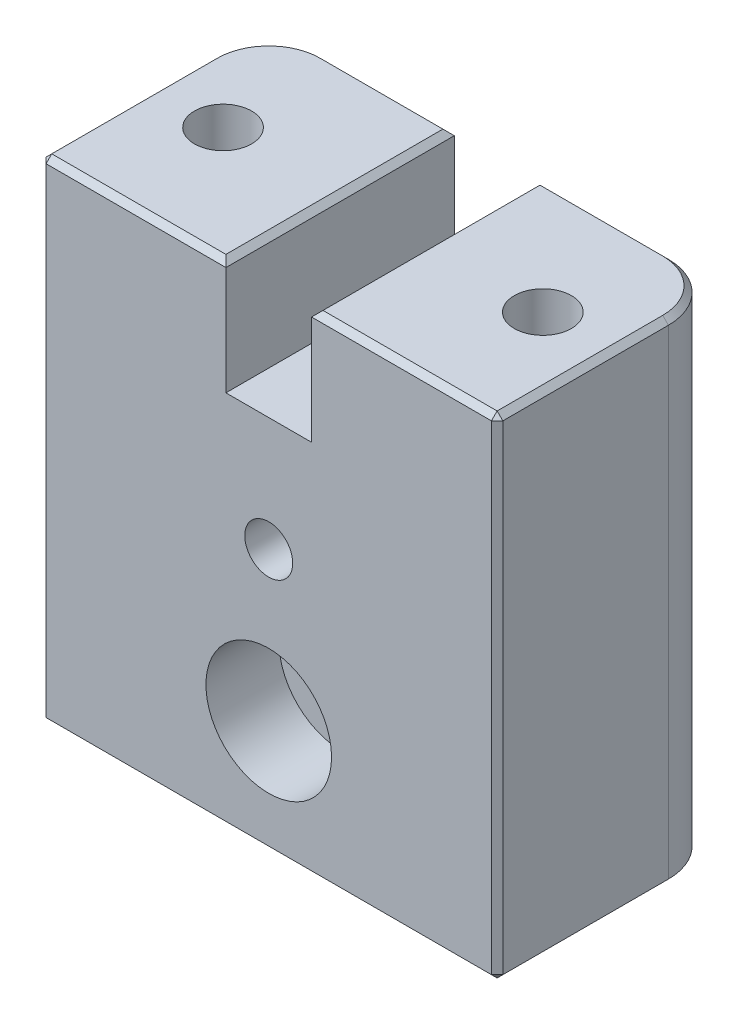
SolidWorks part; units mm, degrees
material "Plain Carbon Steel"
ref_plane "Front Plane" through (0, 0, 0) normal (0, 0, 1) x (1, 0, 0)
ref_plane "Top Plane" through (0, 0, 0) normal (0, 1, 0) x (1, 0, 0)
ref_plane "Right Plane" through (0, 0, 0) normal (1, 0, 0) x (0, 0, -1)
sketch "Sketch1" plane through (0, 0, 0) normal (0, 0, 1) x (1, 0, 0)
  line L1 (-20, -21.5) -> (20, -21.5)
  line L2 (-20, -21.5) -> (-20, 21.5)
  line L3 (-20, 21.5) -> (20, 21.5)
  line L4 (20, -21.5) -> (20, 21.5)
  line L5 (-20, -21.5) -> (20, 21.5) construction
  line L6 (-20, 21.5) -> (20, -21.5) construction
  point P0 (0, 0)
  dimension "D1" = 40
  dimension "D2" = 43
extrude "Boss-Extrude1" add sketch "Sketch1" along normal blind 20
sketch "Sketch2" plane through (0, 21.5, 0) normal (0, 1, 0) x (1, 0, 0)
  line L0 (20, 0) -> (-20, 0) construction
  line L1 (-3.75, 0) -> (3.75, 0)
  line L2 (-3.75, 0) -> (-3.75, -20)
  line L3 (-3.75, -20) -> (3.75, -20)
  line L4 (3.75, 0) -> (3.75, -20)
  line L5 (20, -20) -> (-20, -20) construction
  line L6 (0, 0) -> (0, -20) construction
  dimension "D1" = 7.5
extrude "Cut-Extrude1" cut sketch "Sketch2" against normal blind 10
hole_wizard "M6 Tapped Hole1" positions "Sketch8" profile "Sketch7" tap size "M6" standard "ISO"
sketch "Sketch8" plane through (0, 21.5, 0) normal (0, 1, 0) x (1, 0, 0)
  line L0 (-20, -10) -> (20, -10) construction
  line L1 (-20, -20) -> (-20, 0) construction
  line L2 (20, -20) -> (20, 0) construction
  point P0 (-14, -10)
  point P2 (14, -10)
  dimension "D1" = 6
  dimension "D2" = 6
sketch "Sketch7" plane through (-14, 21.5, 10) normal (1, 0, 0) x (0, 0, 1)
  line L0 (0, 0) -> (0, 16.5022)
  line L1 (0, 16.5022) -> (2.5, 15)
  line L2 (2.5, 15) -> (2.5, 0)
  line L5 (2.5, 0) -> (0, 0)
  line L10 (0, 16.5022) -> (-2.5, 15) construction
  line L11 (0, -6.35) -> (0, 107.95) construction
  dimension "Tap Drill Dia." = 5
  dimension "Tap Drill Depth" = 15
  dimension "Drill Angle" = 118
cosmetic thread "Hole Thread3"
cosmetic thread "Hole Thread4"
fillet "Fillet1" radius 5 2 edges at (-20, 0, 0) (20, 0, 0)
chamfer "Chamfer1" distance 0.5 angle 45 18 edges at (0, -21.5, 0) (-9.375, 21.5, 0) (9.375, 21.5, 0) (-18.5355, -21.5, 1.4645) (18.5355, -21.5, 1.4645) (-18.5355, 21.5, 1.4645) (18.5355, 21.5, 1.4645) (-3.75, 21.5, 10) (3.75, 21.5, 10) (11.875, 21.5, 20) (-11.875, 21.5, 20) (-20, -21.5, 12.5) (20, -21.5, 12.5) (-20, 21.5, 12.5) (20, 21.5, 12.5) (-20, 0, 20) (0, -21.5, 20) (20, 0, 20)
hole_wizard "CBORE for M6 Hex Socket Head Cap Screw1" positions "Sketch27" profile "Sketch13" counterbore size "M6" standard "ISO" end condition through all
sketch "Sketch27" plane through (0, 0, 20) normal (0, 0, 1) x (1, 0, 0)
  line L0 (19.5, -21.5) -> (-19.5, -21.5) construction
  point P0 (0, -11.5)
  dimension "D1" = 10
sketch "Sketch13" plane through (0, -11.5, 20) normal (1, 0, 0) x (0, -1, 0)
  line L0 (0, 0) -> (0, 20)
  line L1 (0, 20) -> (3.2, 20)
  line L3 (3.2, 20) -> (3.2, 6.4)
  line L4 (3.2, 6.4) -> (5.5, 6.4)
  line L5 (5.5, 6.4) -> (5.5, 0)
  line L7 (5.5, 0) -> (0, 0)
  line L11 (0, -6.35) -> (0, 107.95) construction
  dimension "Thru Hole Dia." = 6.4
  dimension "Thru Hole Depth" = 20
  dimension "C'Bore Dia." = 11
  dimension "C'Bore Depth" = 6.4
hole_wizard "M5 Tapped Hole1" positions "Sketch30" profile "Sketch29" tap size "M5" standard "ISO"
sketch "Sketch30" plane through (0, 0, 20) normal (0, 0, 1) x (1, 0, 0)
  point P0 (0, 1.5)
sketch "Sketch29" plane through (0, 1.5, 20) normal (1, 0, 0) x (0, -1, 0)
  line L0 (0, 0) -> (0, 13.6618)
  line L1 (0, 13.6618) -> (2.1, 12.4)
  line L2 (2.1, 12.4) -> (2.1, 0)
  line L5 (2.1, 0) -> (0, 0)
  line L10 (0, 13.6618) -> (-2.1, 12.4) construction
  line L11 (0, -6.35) -> (0, 107.95) construction
  dimension "Tap Drill Dia." = 4.2
  dimension "Tap Drill Depth" = 12.4
  dimension "Drill Angle" = 118
cosmetic thread "Hole Thread5"
